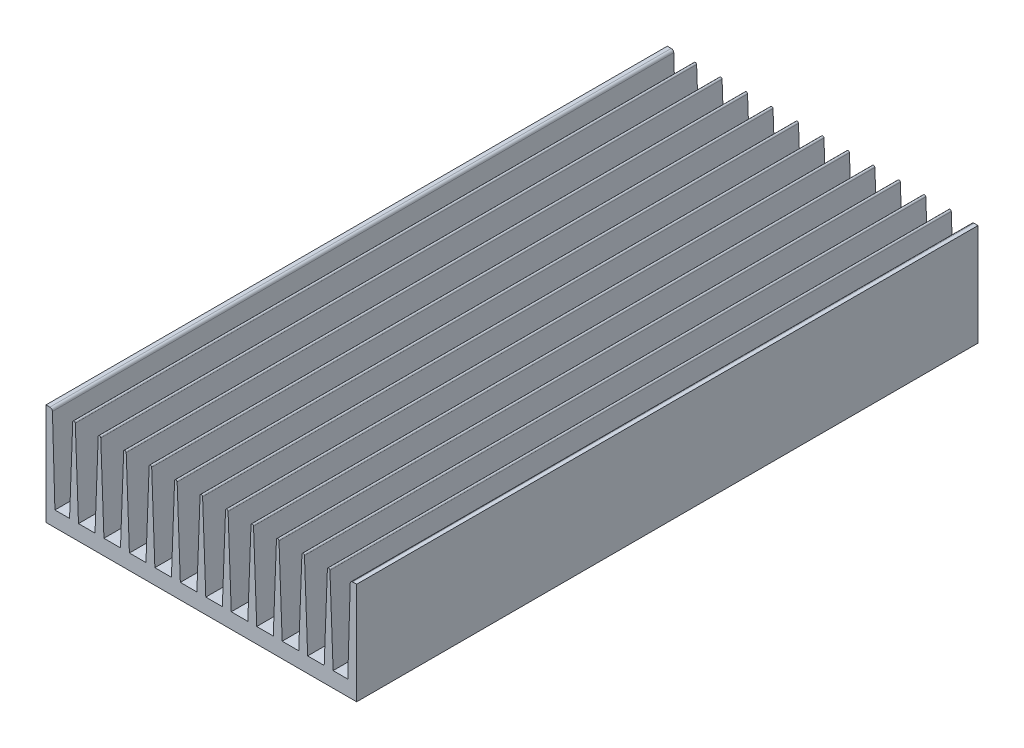
SolidWorks part; units mm, degrees
ref_plane "Спереди" through (0, 0, 0) normal (0, 0, 1) x (1, 0, 0)
ref_plane "Сверху" through (0, 0, 0) normal (0, 1, 0) x (1, 0, 0)
ref_plane "Справа" through (0, 0, 0) normal (1, 0, 0) x (0, 0, -1)
sketch "Эскиз1" plane through (0, 0, 0) normal (0, 0, 1) x (1, 0, 0)
  line L0 (0, 40) -> (1.529, 40)
  line L1 (0, 0) -> (122, 0)
  line L2 (2.5285, 39.0294) -> (3.5, 6)
  line L3 (0, 40) -> (0, 0)
  line L4 (122, 40) -> (122, 0)
  line L5 (61, 63.7127) -> (61, -22.2582) construction
  line L8 (122, 40) -> (120.471, 40)
  line L9 (119.4715, 39.0294) -> (118.5, 6)
  line L10 (3.5, 6) -> (118.5, 6)
  arc A0 (1.529, 40) -> (2.5285, 39.0294) centre (1.529, 39) cw
  arc A2 (120.471, 40) -> (119.4715, 39.0294) centre (120.471, 39) ccw
  point P18 (119.5, 40)
  dimension "D9" = 1
  dimension "D1" = 122
  dimension "D2" = 6
  dimension "D3" = 40
  dimension "D4" = 3.5
  dimension "D7" = 2.5
extrude "Вытянуть1" add sketch "Эскиз1" along normal blind 244
sketch "Эскиз2" plane through (0, 0, 244) normal (0, 0, 1) x (1, 0, 0)
  line L0 (118.5, 6) -> (3.5, 6) construction
  line L1 (10.5, 39.5) -> (9.25, 6)
  line L2 (11, 39.5) -> (11, 22.5548) construction
  line L3 (11.5, 39.5) -> (12.75, 6)
  line L4 (9.25, 6) -> (12.75, 6)
  line L6 (0, 40) -> (0, 0) construction
  arc A0 (10.5, 39.5) -> (11.5, 39.5) centre (11, 39.5) cw
  dimension "D1" = 34
  dimension "D3" = 0.5
  dimension "D2" = 3.5
  dimension "D4" = 11
  dimension "D5" = 1
extrude "Вытянуть3" add sketch "Эскиз2" against normal blind 244
pattern_curve "Кривая1" of "Вытянуть3" along edge at (61, 0, 0) parameters "D1"=11, "D3"=10, "D2"=1, "D4"=50
sketch "Эскиз3" plane through (0, 0, 0) normal (0, -1, 0) x (1, 0, 0)
  line L0 (-14.0506, 236) -> (137.5079, 236) construction
  line L1 (0, 244) -> (122, 244) construction
  line L2 (0, 244) -> (0, 0) construction
  line L3 (-46.7511, 122) -> (151.4312, 122) construction
  line L4 (0, 0) -> (122, 0) construction
  circle A0 centre (26, 236) radius 2.25
  circle A1 centre (96, 236) radius 2.25
  circle A2 centre (96, 8) radius 2.25
  circle A3 centre (26, 8) radius 2.25
  dimension "D2" = 70
  dimension "D4" = 4.5
  dimension "D1" = 8
  dimension "D3" = 26
extrude "Вырез-Вытянуть1" cut sketch "Эскиз3" against normal blind 6
sketch "Эскиз4" plane through (133.2401, 0, 310.1491) normal (0, -1, 0) x (-1, 0, 0)
  line L0 (48.7401, 229.1491) -> (48.7401, 87.5745) construction
  line L1 (133.2401, 66.1491) -> (133.2401, 310.1491) construction
  line L2 (133.2401, 66.1491) -> (11.2401, 66.1491) construction
  line L3 (25.2401, 240.1491) -> (91.2401, 240.1491) construction
  line L4 (25.2401, 240.1491) -> (25.2401, 288.1491) construction
  line L5 (25.2401, 288.1491) -> (91.2401, 288.1491) construction
  line L6 (91.2401, 240.1491) -> (91.2401, 288.1491) construction
  line L7 (133.2401, 310.1491) -> (11.2401, 310.1491) construction
  line L8 (81.7401, 168.1491) -> (81.7401, 187.1491) construction
  circle A0 centre (48.7401, 89.1491) radius 1.6
  circle A1 centre (48.7401, 229.1491) radius 1.6
  circle A2 centre (8.9901, 225.5491) radius 1.6
  circle A3 centre (66.5101, 102.1491) radius 1.15
  circle A4 centre (81.7401, 187.1491) radius 1.6
  circle A5 centre (91.2401, 288.1491) radius 1.6
  circle A6 centre (91.2401, 240.1491) radius 1.6
  circle A7 centre (25.2401, 240.1491) radius 1.6
  circle A8 centre (25.2401, 288.1491) radius 1.6
  circle A9 centre (81.7401, 168.1491) radius 1.6
  dimension "D1" = 3.2
  dimension "D3" = 3.2
  dimension "D4" = 39.75
  dimension "D5" = 36
  dimension "D6" = 2.3
  dimension "D7" = 3.2
  dimension "D8" = 3.6
  dimension "D9" = 140
  dimension "D10" = 84.5
  dimension "D11" = 23
  dimension "D16" = 33
  dimension "D17" = 121
  dimension "D2" = 66.73
  dimension "D18" = 102
  dimension "D12" = 66
  dimension "D13" = 48
  dimension "D14" = 22
  dimension "D15" = 42
extrude "Вырез-Вытянуть2" cut sketch "Эскиз4" against normal blind 6
cosmetic thread "Условное изображение резьбы5" parameters "D2"=4
cosmetic thread "Условное изображение резьбы6" parameters "D2"=4
cosmetic thread "Условное изображение резьбы10" parameters "D2"=4
cosmetic thread "Условное изображение резьбы11" parameters "D2"=4
cosmetic thread "Условное изображение резьбы12" parameters "D2"=4
cosmetic thread "Условное изображение резьбы13" parameters "D2"=4
cosmetic thread "Условное изображение резьбы14" parameters "D2"=3
cosmetic thread "Условное изображение резьбы15" parameters "D2"=4
cosmetic thread "Условное изображение резьбы16" parameters "D2"=4
